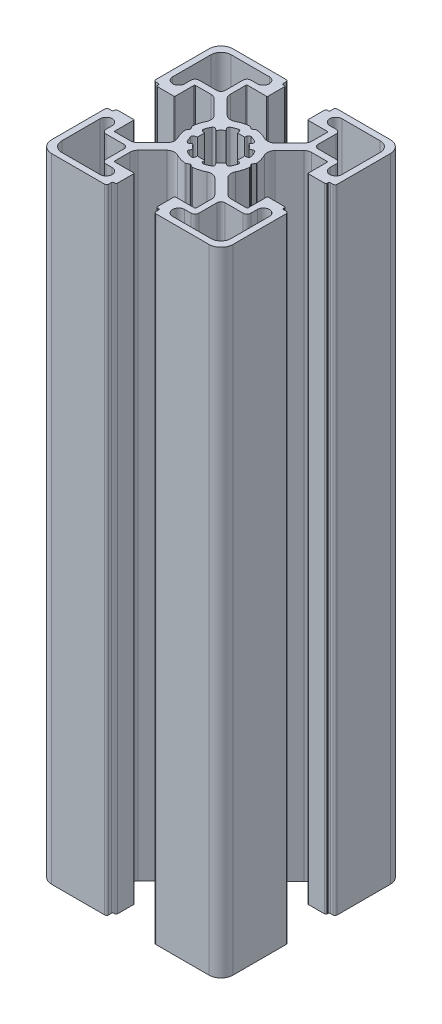
SolidWorks part; units mm, degrees
ref_plane "Front Plane" through (0, 0, 0) normal (0, 0, 1) x (1, 0, 0)
ref_plane "Top Plane" through (0, 0, 0) normal (0, 1, 0) x (1, 0, 0)
ref_plane "Right Plane" through (0, 0, 0) normal (1, 0, 0) x (0, 0, -1)
sketch "Sketch1" plane through (0, 0, 0) normal (0, 1, 0) x (1, 0, 0)
  line L106 (-18, 9.0002) -> (-18, 10.55)
  line L107 (-21, 18.5) -> (-21, 9.0002)
  line L108 (-9, 21) -> (-18.5, 21)
  line L109 (-10.55, 18) -> (-9, 18)
  line L110 (0.9675, 5.4811) -> (0.8674, 4.9242)
  line L111 (2.864, 4.0985) -> (3.1913, 4.5626)
  line L112 (4.5668, 3.2081) -> (4.0897, 2.8765)
  line L113 (4.9205, 0.8878) -> (5.4897, 0.9862)
  line L114 (5.4898, -0.9862) -> (4.9205, -0.8878)
  line L115 (4.0897, -2.8765) -> (4.5668, -3.2082)
  line L116 (3.1914, -4.5627) -> (2.864, -4.0985)
  line L117 (0.8674, -4.9242) -> (0.9675, -5.4811)
  line L118 (-0.9675, -5.4811) -> (-0.8674, -4.9242)
  line L119 (-2.864, -4.0985) -> (-3.1913, -4.5626)
  line L120 (-4.5668, -3.2082) -> (-4.0897, -2.8765)
  line L121 (-4.9205, -0.8878) -> (-5.4897, -0.9862)
  line L122 (-5.4899, 0.9862) -> (-4.9205, 0.8878)
  line L123 (-4.0897, 2.8765) -> (-4.5668, 3.2081)
  line L124 (-3.1914, 4.5627) -> (-2.864, 4.0985)
  line L125 (-0.8674, 4.9242) -> (-0.9675, 5.4811)
  line L126 (-11.55, 12.55) -> (-11.55, 17)
  line L127 (-17, 11.55) -> (-12.55, 11.55)
  line L128 (-21, -9.0002) -> (-21, -18.5)
  line L129 (-18, -10.55) -> (-18, -9.0002)
  line L130 (-12.55, -11.55) -> (-17, -11.55)
  line L131 (-11.55, -17) -> (-11.55, -12.55)
  line L132 (-9, -18) -> (-10.55, -18)
  line L133 (-18.5, -21) -> (-9, -21)
  line L134 (21, 9.0002) -> (21, 18.5)
  line L135 (18, 10.55) -> (18, 9.0002)
  line L136 (12.55, 11.55) -> (17, 11.55)
  line L137 (11.55, 17) -> (11.55, 12.55)
  line L138 (9, 18) -> (10.55, 18)
  line L139 (18.5, 21) -> (9, 21)
  line L140 (17, -11.55) -> (12.55, -11.55)
  line L141 (18, -9.0002) -> (18, -10.55)
  line L142 (21, -18.5) -> (21, -9.0002)
  line L143 (9, -21) -> (18.5, -21)
  line L144 (10.55, -18) -> (9, -18)
  line L145 (11.55, -12.55) -> (11.55, -17)
  line L146 (7.5635, 5.8587) -> (11.1298, 9.425)
  line L147 (12.5048, 9.9945) -> (16.3169, 9.9945)
  line L148 (16.5169, 9.7945) -> (16.5169, 5.2)
  line L149 (16.7169, 5) -> (20.7196, 5)
  line L150 (21.0196, 5.3) -> (21.0196, 5.5)
  line L151 (21.3196, 5.8) -> (22, 5.8)
  line L152 (22.5, 6.3) -> (22.5, 19.5)
  line L153 (19.5, 22.5) -> (6.3757, 22.5)
  line L154 (5.8757, 22) -> (5.8757, 21.3)
  line L155 (5.5757, 21) -> (5.3, 21)
  line L156 (5, 20.7) -> (5, 16.6668)
  line L157 (5.2, 16.4668) -> (9.9054, 16.4668)
  line L158 (10.1054, 16.2668) -> (10.1054, 12.4716)
  line L159 (9.5196, 11.0574) -> (5.9449, 7.4827)
  line L160 (0.7548, 7.9748) -> (0.1126, 7.6069)
  line L161 (-0.1126, 7.6069) -> (-0.7547, 7.9748)
  line L162 (-5.9449, 7.4827) -> (-9.5196, 11.0574)
  line L163 (-10.1054, 12.4716) -> (-10.1054, 16.2668)
  line L164 (-9.9054, 16.4668) -> (-5.2, 16.4668)
  line L165 (-5, 16.6668) -> (-5, 20.7)
  line L166 (-5.3, 21) -> (-5.5757, 21)
  line L167 (-5.8757, 21.3) -> (-5.8757, 22)
  line L168 (-6.3757, 22.5) -> (-19.5, 22.5)
  line L169 (-22.5, 19.5) -> (-22.5, 6.3)
  line L170 (-22, 5.8) -> (-21.3196, 5.8)
  line L171 (-21.0196, 5.5) -> (-21.0196, 5.3)
  line L172 (-20.7196, 5) -> (-16.7169, 5)
  line L173 (-16.5169, 5.2) -> (-16.5169, 9.7945)
  line L174 (-16.3169, 9.9945) -> (-12.5048, 9.9945)
  line L175 (-11.1298, 9.425) -> (-7.5635, 5.8587)
  line L176 (-7.974, 0.7926) -> (-7.5401, 0.0468)
  line L177 (-7.5401, -0.0468) -> (-7.974, -0.7926)
  line L178 (-7.5635, -5.8587) -> (-11.1298, -9.425)
  line L179 (-12.5048, -9.9945) -> (-16.3169, -9.9945)
  line L180 (-16.5169, -9.7945) -> (-16.5169, -5.2)
  line L181 (-16.7169, -5) -> (-20.7196, -5)
  line L182 (-21.0196, -5.3) -> (-21.0196, -5.5)
  line L183 (-21.3196, -5.8) -> (-22, -5.8)
  line L184 (-22.5, -6.3) -> (-22.5, -19.5)
  line L185 (-19.5, -22.5) -> (-6.3757, -22.5)
  line L186 (-5.8757, -22) -> (-5.8757, -21.3)
  line L187 (-5.5757, -21) -> (-5.3, -21)
  line L188 (-5, -20.7) -> (-5, -16.6668)
  line L189 (-5.2, -16.4668) -> (-9.9054, -16.4668)
  line L190 (-10.1054, -16.2668) -> (-10.1054, -12.4716)
  line L191 (-9.5196, -11.0574) -> (-5.9449, -7.4827)
  line L192 (-0.7547, -7.9748) -> (-0.1126, -7.6069)
  line L193 (0.1126, -7.6069) -> (0.7548, -7.9748)
  line L194 (5.9449, -7.4827) -> (9.5196, -11.0574)
  line L195 (10.1054, -12.4716) -> (10.1054, -16.2668)
  line L196 (9.9054, -16.4668) -> (5.2, -16.4668)
  line L197 (5, -16.6668) -> (5, -20.7)
  line L198 (5.3, -21) -> (5.5757, -21)
  line L199 (5.8757, -21.3) -> (5.8757, -22)
  line L200 (6.3757, -22.5) -> (19.5, -22.5)
  line L201 (22.5, -19.5) -> (22.5, -6.3)
  line L202 (22, -5.8) -> (21.3196, -5.8)
  line L203 (21.0196, -5.5) -> (21.0196, -5.3)
  line L204 (20.7196, -5) -> (16.7169, -5)
  line L205 (16.5169, -5.2) -> (16.5169, -9.7945)
  line L206 (16.3169, -9.9945) -> (12.5048, -9.9945)
  line L207 (11.1298, -9.425) -> (7.5635, -5.8587)
  line L208 (7.974, -0.7926) -> (7.5401, -0.0468)
  line L209 (7.5401, 0.0468) -> (7.974, 0.7926)
  arc A140 (-17, 11.55) -> (-18, 10.55) centre (-17, 10.55) ccw
  arc A141 (-21, 9.0002) -> (-18, 9.0002) centre (-19.5, 9.0002) ccw
  arc A142 (-18.5, 21) -> (-21, 18.5) centre (-18.5, 18.5) ccw
  arc A143 (-9, 18) -> (-9, 21) centre (-9, 19.5) ccw
  arc A144 (-10.55, 18) -> (-11.55, 17) centre (-10.55, 17) ccw
  arc A145 (-12.55, 11.55) -> (-11.55, 12.55) centre (-12.55, 12.55) ccw
  arc A146 (-21, -18.5) -> (-18.5, -21) centre (-18.5, -18.5) ccw
  arc A147 (-18, -9.0002) -> (-21, -9.0002) centre (-19.5, -9.0002) ccw
  arc A148 (-18, -10.55) -> (-17, -11.55) centre (-17, -10.55) ccw
  arc A149 (-11.55, -12.55) -> (-12.55, -11.55) centre (-12.55, -12.55) ccw
  arc A150 (-11.55, -17) -> (-10.55, -18) centre (-10.55, -17) ccw
  arc A151 (-9, -21) -> (-9, -18) centre (-9, -19.5) ccw
  arc A152 (0.8674, 4.9242) -> (-0.8674, 4.9242) centre (0, 0) ccw
  arc A153 (1.5951, 5.8941) -> (0.9675, 5.4811) centre (1.4627, 5.4119) ccw
  arc A154 (3.0417, 5.301) -> (1.5951, 5.8941) centre (0.0235, 0) ccw
  arc A155 (3.1913, 4.5626) -> (3.0417, 5.301) centre (2.7943, 4.8665) ccw
  arc A156 (4.0897, 2.8765) -> (2.864, 4.0985) centre (0, 0) ccw
  arc A157 (5.3025, 3.0565) -> (4.5668, 3.2081) centre (4.868, 2.8091) ccw
  arc A158 (5.906, 1.6142) -> (5.3025, 3.0565) centre (0.0235, 0) ccw
  arc A159 (5.4897, 0.9862) -> (5.906, 1.6142) centre (5.4239, 1.4819) ccw
  arc A160 (4.9205, -0.8878) -> (4.9205, 0.8878) centre (0, 0) ccw
  arc A161 (5.906, -1.6142) -> (5.4898, -0.9862) centre (5.4239, -1.4819) ccw
  arc A162 (5.3025, -3.0564) -> (5.906, -1.6142) centre (0.0235, 0) ccw
  arc A163 (4.5668, -3.2082) -> (5.3025, -3.0564) centre (4.868, -2.8091) ccw
  arc A164 (2.864, -4.0985) -> (4.0897, -2.8765) centre (0, 0) ccw
  arc A165 (3.0416, -5.301) -> (3.1914, -4.5627) centre (2.7943, -4.8665) ccw
  arc A166 (1.5951, -5.8941) -> (3.0416, -5.301) centre (0.0235, 0) ccw
  arc A167 (0.9675, -5.4811) -> (1.5951, -5.8941) centre (1.4627, -5.4119) ccw
  arc A168 (-0.8674, -4.9242) -> (0.8674, -4.9242) centre (0, 0) ccw
  arc A169 (-1.5951, -5.8941) -> (-0.9675, -5.4811) centre (-1.4627, -5.4119) ccw
  arc A170 (-3.0416, -5.301) -> (-1.5951, -5.8941) centre (-0.0235, 0) ccw
  arc A171 (-3.1913, -4.5626) -> (-3.0416, -5.301) centre (-2.7943, -4.8665) ccw
  arc A172 (-4.0897, -2.8765) -> (-2.864, -4.0985) centre (0, 0) ccw
  arc A173 (-5.3025, -3.0565) -> (-4.5668, -3.2082) centre (-4.868, -2.8091) ccw
  arc A174 (-5.906, -1.6142) -> (-5.3025, -3.0565) centre (-0.0235, 0) ccw
  arc A175 (-5.4897, -0.9862) -> (-5.906, -1.6142) centre (-5.4239, -1.4819) ccw
  arc A176 (-4.9205, 0.8878) -> (-4.9205, -0.8878) centre (0, 0) ccw
  arc A177 (-5.906, 1.6141) -> (-5.4899, 0.9862) centre (-5.4239, 1.4818) ccw
  arc A178 (-5.3025, 3.0564) -> (-5.906, 1.6141) centre (-0.0235, 0) ccw
  arc A179 (-4.5668, 3.2081) -> (-5.3025, 3.0564) centre (-4.868, 2.8091) ccw
  arc A180 (-2.864, 4.0985) -> (-4.0897, 2.8765) centre (0, 0) ccw
  arc A181 (-3.0417, 5.301) -> (-3.1914, 4.5627) centre (-2.7943, 4.8665) ccw
  arc A182 (-1.5951, 5.8941) -> (-3.0417, 5.301) centre (-0.0235, 0) ccw
  arc A183 (-0.9675, 5.4811) -> (-1.5951, 5.8941) centre (-1.4627, 5.4119) ccw
  arc A184 (21, 18.5) -> (18.5, 21) centre (18.5, 18.5) ccw
  arc A185 (18, 9.0002) -> (21, 9.0002) centre (19.5, 9.0002) ccw
  arc A186 (18, 10.55) -> (17, 11.55) centre (17, 10.55) ccw
  arc A187 (11.55, 12.55) -> (12.55, 11.55) centre (12.55, 12.55) ccw
  arc A188 (11.55, 17) -> (10.55, 18) centre (10.55, 17) ccw
  arc A189 (9, 21) -> (9, 18) centre (9, 19.5) ccw
  arc A190 (12.55, -11.55) -> (11.55, -12.55) centre (12.55, -12.55) ccw
  arc A191 (17, -11.55) -> (18, -10.55) centre (17, -10.55) ccw
  arc A192 (21, -9.0002) -> (18, -9.0002) centre (19.5, -9.0002) ccw
  arc A193 (18.5, -21) -> (21, -18.5) centre (18.5, -18.5) ccw
  arc A194 (9, -18) -> (9, -21) centre (9, -19.5) ccw
  arc A195 (10.55, -18) -> (11.55, -17) centre (10.55, -17) ccw
  arc A196 (7.9999, 0.9154) -> (7.2004, 3.6119) centre (0.0496, 0.0249) ccw
  arc A197 (7.5635, 5.8587) -> (7.2004, 3.6119) centre (8.9385, 4.4837) ccw
  arc A198 (12.5048, 9.9945) -> (11.1298, 9.425) centre (12.5048, 8.05) ccw
  arc A199 (16.5169, 9.7945) -> (16.3169, 9.9945) centre (16.3169, 9.7945) ccw
  arc A200 (16.5169, 5.2) -> (16.7169, 5) centre (16.7169, 5.2) ccw
  arc A201 (20.7196, 5) -> (21.0196, 5.3) centre (20.7196, 5.3) ccw
  arc A202 (21.3196, 5.8) -> (21.0196, 5.5) centre (21.3196, 5.5) ccw
  arc A203 (22, 5.8) -> (22.5, 6.3) centre (22, 6.3) ccw
  arc A204 (22.5, 19.5) -> (19.5, 22.5) centre (19.5, 19.5) ccw
  arc A205 (6.3757, 22.5) -> (5.8757, 22) centre (6.3757, 22) ccw
  arc A206 (5.5757, 21) -> (5.8757, 21.3) centre (5.5757, 21.3) ccw
  arc A207 (5.3, 21) -> (5, 20.7) centre (5.3, 20.7) ccw
  arc A208 (5, 16.6668) -> (5.2, 16.4668) centre (5.2, 16.6668) ccw
  arc A209 (10.1054, 16.2668) -> (9.9054, 16.4668) centre (9.9054, 16.2668) ccw
  arc A210 (9.5196, 11.0574) -> (10.1054, 12.4716) centre (8.1054, 12.4716) ccw
  arc A211 (3.6665, 7.1733) -> (5.9449, 7.4827) centre (4.5855, 8.9496) ccw
  arc A212 (3.6665, 7.1733) -> (0.8753, 8.0001) centre (0.0235, 0) ccw
  arc A213 (0.8753, 8.0001) -> (0.7548, 7.9748) centre (0.8542, 7.8013) ccw
  arc A214 (0, 7.531) -> (0.1126, 7.6069) centre (-0.0489, 7.7249) ccw
  arc A215 (-0.1126, 7.6069) -> (0, 7.531) centre (0.0489, 7.7249) ccw
  arc A216 (-0.7547, 7.9748) -> (-0.8753, 8.0001) centre (-0.8542, 7.8013) ccw
  arc A217 (-0.8753, 8.0001) -> (-3.6665, 7.1733) centre (-0.0235, 0) ccw
  arc A218 (-5.9449, 7.4827) -> (-3.6665, 7.1733) centre (-4.5855, 8.9496) ccw
  arc A219 (-10.1054, 12.4716) -> (-9.5196, 11.0574) centre (-8.1054, 12.4716) ccw
  arc A220 (-9.9054, 16.4668) -> (-10.1054, 16.2668) centre (-9.9054, 16.2668) ccw
  arc A221 (-5.2, 16.4668) -> (-5, 16.6668) centre (-5.2, 16.6668) ccw
  arc A222 (-5, 20.7) -> (-5.3, 21) centre (-5.3, 20.7) ccw
  arc A223 (-5.8757, 21.3) -> (-5.5757, 21) centre (-5.5757, 21.3) ccw
  arc A224 (-5.8757, 22) -> (-6.3757, 22.5) centre (-6.3757, 22) ccw
  arc A225 (-19.5, 22.5) -> (-22.5, 19.5) centre (-19.5, 19.5) ccw
  arc A226 (-22.5, 6.3) -> (-22, 5.8) centre (-22, 6.3) ccw
  arc A227 (-21.0196, 5.5) -> (-21.3196, 5.8) centre (-21.3196, 5.5) ccw
  arc A228 (-21.0196, 5.3) -> (-20.7196, 5) centre (-20.7196, 5.3) ccw
  arc A229 (-16.7169, 5) -> (-16.5169, 5.2) centre (-16.7169, 5.2) ccw
  arc A230 (-16.3169, 9.9945) -> (-16.5169, 9.7945) centre (-16.3169, 9.7945) ccw
  arc A231 (-11.1298, 9.425) -> (-12.5048, 9.9945) centre (-12.5048, 8.05) ccw
  arc A232 (-7.2004, 3.6119) -> (-7.5635, 5.8587) centre (-8.9385, 4.4837) ccw
  arc A233 (-7.2004, 3.6119) -> (-7.9999, 0.9154) centre (-0.0496, 0.0249) ccw
  arc A234 (-7.9999, 0.9154) -> (-7.974, 0.7926) centre (-7.8011, 0.8932) ccw
  arc A235 (-7.5313, 0) -> (-7.5401, 0.0468) centre (-7.7309, -0.013) ccw
  arc A236 (-7.5401, -0.0468) -> (-7.5313, 0) centre (-7.7309, 0.013) ccw
  arc A237 (-7.974, -0.7926) -> (-7.9999, -0.9154) centre (-7.8011, -0.8932) ccw
  arc A238 (-7.9999, -0.9154) -> (-7.2004, -3.6119) centre (-0.0496, -0.0249) ccw
  arc A239 (-7.5635, -5.8587) -> (-7.2004, -3.6119) centre (-8.9385, -4.4837) ccw
  arc A240 (-12.5048, -9.9945) -> (-11.1298, -9.425) centre (-12.5048, -8.05) ccw
  arc A241 (-16.5169, -9.7945) -> (-16.3169, -9.9945) centre (-16.3169, -9.7945) ccw
  arc A242 (-16.5169, -5.2) -> (-16.7169, -5) centre (-16.7169, -5.2) ccw
  arc A243 (-20.7196, -5) -> (-21.0196, -5.3) centre (-20.7196, -5.3) ccw
  arc A244 (-21.3196, -5.8) -> (-21.0196, -5.5) centre (-21.3196, -5.5) ccw
  arc A245 (-22, -5.8) -> (-22.5, -6.3) centre (-22, -6.3) ccw
  arc A246 (-22.5, -19.5) -> (-19.5, -22.5) centre (-19.5, -19.5) ccw
  arc A247 (-6.3757, -22.5) -> (-5.8757, -22) centre (-6.3757, -22) ccw
  arc A248 (-5.5757, -21) -> (-5.8757, -21.3) centre (-5.5757, -21.3) ccw
  arc A249 (-5.3, -21) -> (-5, -20.7) centre (-5.3, -20.7) ccw
  arc A250 (-5, -16.6668) -> (-5.2, -16.4668) centre (-5.2, -16.6668) ccw
  arc A251 (-10.1054, -16.2668) -> (-9.9054, -16.4668) centre (-9.9054, -16.2668) ccw
  arc A252 (-9.5196, -11.0574) -> (-10.1054, -12.4716) centre (-8.1054, -12.4716) ccw
  arc A253 (-3.6665, -7.1733) -> (-5.9449, -7.4827) centre (-4.5855, -8.9496) ccw
  arc A254 (-3.6665, -7.1733) -> (-0.8753, -8.0001) centre (-0.0235, 0) ccw
  arc A255 (-0.8753, -8.0001) -> (-0.7547, -7.9748) centre (-0.8542, -7.8013) ccw
  arc A256 (0, -7.531) -> (-0.1126, -7.6069) centre (0.0489, -7.7249) ccw
  arc A257 (0.1126, -7.6069) -> (0, -7.531) centre (-0.0489, -7.7249) ccw
  arc A258 (0.7548, -7.9748) -> (0.8753, -8.0001) centre (0.8542, -7.8012) ccw
  arc A259 (0.8753, -8.0001) -> (3.6665, -7.1733) centre (0.0235, 0) ccw
  arc A260 (5.9449, -7.4827) -> (3.6665, -7.1733) centre (4.5855, -8.9496) ccw
  arc A261 (10.1054, -12.4716) -> (9.5196, -11.0574) centre (8.1054, -12.4716) ccw
  arc A262 (9.9054, -16.4668) -> (10.1054, -16.2668) centre (9.9054, -16.2668) ccw
  arc A263 (5.2, -16.4668) -> (5, -16.6668) centre (5.2, -16.6668) ccw
  arc A264 (5, -20.7) -> (5.3, -21) centre (5.3, -20.7) ccw
  arc A265 (5.8757, -21.3) -> (5.5757, -21) centre (5.5757, -21.3) ccw
  arc A266 (5.8757, -22) -> (6.3757, -22.5) centre (6.3757, -22) ccw
  arc A267 (19.5, -22.5) -> (22.5, -19.5) centre (19.5, -19.5) ccw
  arc A268 (22.5, -6.3) -> (22, -5.8) centre (22, -6.3) ccw
  arc A269 (21.0196, -5.5) -> (21.3196, -5.8) centre (21.3196, -5.5) ccw
  arc A270 (21.0196, -5.3) -> (20.7196, -5) centre (20.7196, -5.3) ccw
  arc A271 (16.7169, -5) -> (16.5169, -5.2) centre (16.7169, -5.2) ccw
  arc A272 (16.3169, -9.9945) -> (16.5169, -9.7945) centre (16.3169, -9.7945) ccw
  arc A273 (11.1298, -9.425) -> (12.5048, -9.9945) centre (12.5048, -8.05) ccw
  arc A274 (7.2004, -3.6119) -> (7.5635, -5.8587) centre (8.9385, -4.4837) ccw
  arc A275 (7.2004, -3.6119) -> (7.9999, -0.9154) centre (0.0496, -0.0249) ccw
  arc A276 (7.9999, -0.9154) -> (7.974, -0.7926) centre (7.8011, -0.8932) ccw
  arc A277 (7.5313, 0) -> (7.5401, -0.0468) centre (7.7309, 0.013) ccw
  arc A278 (7.5401, 0.0468) -> (7.5313, 0) centre (7.7309, -0.013) ccw
  arc A279 (7.974, 0.7926) -> (7.9999, 0.9154) centre (7.8011, 0.8932) ccw
extrude "Boss-Extrude1" add sketch "Sketch1" along normal blind 157
